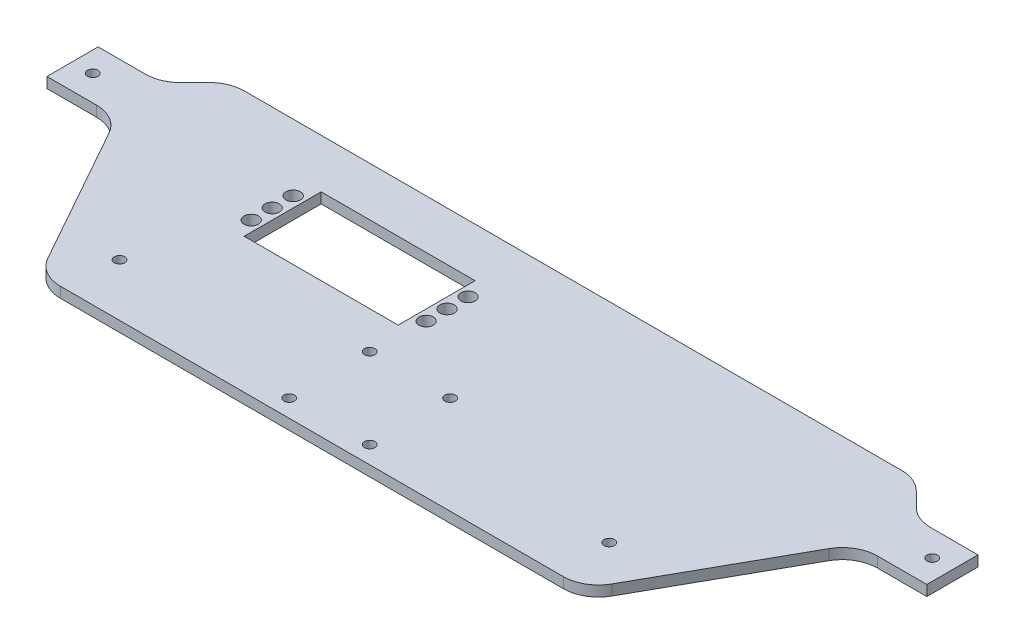
SolidWorks part; units mm, degrees
ref_plane "Alzado" through (0, 0, 0) normal (0, 0, 1) x (1, 0, 0)
ref_plane "Planta" through (0, 0, 0) normal (0, 1, 0) x (1, 0, 0)
ref_plane "Vista lateral" through (0, 0, 0) normal (1, 0, 0) x (0, 0, -1)
sketch "Croquis1" plane through (0, 0, 0) normal (0, 1, 0) x (1, 0, 0)
  line L0 (-27.8825, 0) -> (38.5584, 0) construction
  line L1 (-88.1, 42.3182) -> (88.1, 42.3182)
  line L2 (-77.75, -42.3182) -> (77.75, -42.3182)
  line L3 (-88.1, 42.3182) -> (-108.1, 22.3182)
  line L4 (-108.1, 22.3182) -> (-127.75, 22.3182)
  line L5 (0, 0) -> (0, 27.7067) construction
  line L6 (-127.75, 22.3182) -> (-127.75, 7.6818)
  line L7 (-127.75, 7.6818) -> (-105.75, 7.6818)
  line L8 (-105.75, 7.6818) -> (-77.75, -42.3182)
  line L9 (88.1, 42.3182) -> (108.1, 22.3182)
  line L10 (108.1, 22.3182) -> (127.75, 22.3182)
  line L11 (127.75, 22.3182) -> (127.75, 7.6818)
  line L12 (127.75, 7.6818) -> (105.75, 7.6818)
  line L13 (105.75, 7.6818) -> (77.75, -42.3182)
  dimension "D1" = 255.5
  dimension "D2" = 84.6363
  dimension "D3" = 19.65
  dimension "D4" = 22
  dimension "D5" = 22
  dimension "D6" = 50
  dimension "D7" = 50
  dimension "D8" = 50
  dimension "D9" = 20
  dimension "D10" = 20
  dimension "D11" = 19.65
extrude "Saliente-Extruir1" add sketch "Croquis1" along normal blind 3
fillet "Redondeo1" radius 10 8 edges at (88.1, 1.5, -42.3182) (-88.1, 1.5, -42.3182) (-77.75, 1.5, 42.3182) (77.75, 1.5, 42.3182) (108.1, 1.5, -22.3182) (105.75, 1.5, -7.6818) (-105.75, 1.5, -7.6818) (-108.1, 1.5, -22.3182)
sketch "Croquis2" plane through (0, 3, 0) normal (0, 1, 0) x (1, 0, 0)
  line L0 (0, 0) -> (0, -87.7887) construction
  line L1 (-119.9961, 22.3182) -> (-119.9961, 40.4374) construction
  line L2 (-112.2421, 22.3182) -> (-127.75, 22.3182) construction
  line L3 (-127.75, 15) -> (-123.2915, 15) construction
  line L4 (-127.75, 22.3182) -> (-127.75, 7.6818) construction
  line L5 (119.9961, 22.3182) -> (119.9961, 29.1715) construction
  line L6 (127.75, 22.3182) -> (112.2421, 22.3182) construction
  line L7 (115.6048, 15) -> (126.3231, 15) construction
  line L8 (83.9579, 42.3182) -> (-83.9579, 42.3182) construction
  line L9 (-57, 17.3182) -> (-15, 17.3182)
  line L10 (-71.8888, -42.3182) -> (71.8888, -42.3182) construction
  line L11 (-15, 17.3182) -> (-15, -2.6818)
  line L12 (-15, -2.6818) -> (-57, -2.6818)
  line L13 (-57, -2.6818) -> (-57, 17.3182)
  line L14 (-57, 7.3182) -> (-2.6959, 7.3182) construction
  line L15 (-36, 17.3182) -> (-36, 33.9331) construction
  line L16 (-11, 7.3182) -> (-11, 14.1752) construction
  line L17 (-61, 7.3182) -> (-61, 4.4352) construction
  circle A0 centre (70, -27.3182) radius 1.5
  circle A1 centre (-70, -27.3182) radius 1.5
  circle A2 centre (-119.9961, 15) radius 1.5
  circle A3 centre (119.9961, 15) radius 1.5
  circle A6 centre (-11.5, -14.3182) radius 1.5
  circle A7 centre (11.5, -14.3182) radius 1.5
  circle A8 centre (-11.5, -37.3182) radius 1.5
  circle A9 centre (11.5, -37.3182) radius 1.5
  circle A10 centre (-61, 7.3182) radius 2.05
  circle A11 centre (-11, 7.3182) radius 2.05
  circle A12 centre (-61, 13.3182) radius 2.05
  circle A13 centre (-61, 1.3182) radius 2.05
  circle A14 centre (-11, 13.3182) radius 2.05
  circle A15 centre (-11, 1.3182) radius 2.05
  dimension "D1" = 3
  dimension "D2" = 3
  dimension "D10" = 3
  dimension "D11" = 3
  dimension "D17" = 3
  dimension "D18" = 3
  dimension "D19" = 3
  dimension "D20" = 3
  dimension "D25" = 50
  dimension "D27" = 4.1
  dimension "D28" = 4.1
  dimension "D29" = 4.1
  dimension "D30" = 4.1
  dimension "D31" = 4.1
  dimension "D32" = 4.1
  dimension "D9" = 140
  dimension "D12" = 15
  dimension "D13" = 23
  dimension "D14" = 23
  dimension "D15" = 5
  dimension "D16" = 23
  dimension "D21" = 42
  dimension "D22" = 20
  dimension "D23" = 30
  dimension "D24" = 25
  dimension "D26" = 50
  dimension "D33" = 6
  dimension "D34" = 6
  dimension "D35" = 6
  dimension "D36" = 6
extrude "Cortar-Extruir1" cut sketch "Croquis2" against normal through all
sketch "Croquis3" plane through (0, 3, 0) normal (0, 1, 0) x (1, 0, 0)
  line L0 (-123.75, 22.3182) -> (-123.75, 7.6818)
  line L1 (-112.2421, 22.3182) -> (-127.75, 22.3182) construction
  line L2 (-127.75, 7.6818) -> (-111.6112, 7.6818) construction
  line L3 (-123.75, 7.6818) -> (-127.75, 7.6818)
  line L4 (-127.75, 7.6818) -> (-127.75, 22.3182)
  line L5 (-127.75, 22.3182) -> (-123.75, 22.3182)
  line L6 (127.75, 7.6818) -> (127.75, 22.3182)
  line L7 (127.75, 22.3182) -> (123.75, 22.3182)
  line L8 (127.75, 22.3182) -> (112.2421, 22.3182) construction
  line L9 (123.75, 22.3182) -> (123.75, 7.6818)
  line L10 (111.6112, 7.6818) -> (127.75, 7.6818) construction
  line L11 (123.75, 7.6818) -> (127.75, 7.6818)
  dimension "D1" = 4
  dimension "D2" = 4
extrude "Cortar-Extruir2" cut sketch "Croquis3" against normal through all
sketch "Croquis4" plane through (0, 3, 0) normal (0, 1, 0) x (1, 0, 0)
  line L0 (-36, 17.3182) -> (-36, -16.9775) construction
  line L1 (-15, 17.3182) -> (-57, 17.3182) construction
  line L2 (-57, 7.3182) -> (-47.1795, 7.3182) construction
  line L3 (-57, 17.3182) -> (-57, -2.6818) construction
  line L4 (-58, 18.3182) -> (-58, -3.6818)
  line L5 (-58, -3.6818) -> (-14, -3.6818)
  line L6 (-14, -3.6818) -> (-14, 18.3182)
  line L7 (-58, 18.3182) -> (-14, 18.3182)
  line L8 (-15, -2.6818) -> (-15, 17.3182) construction
  line L9 (-57, -2.6818) -> (-15, -2.6818) construction
  dimension "D1" = 1
  dimension "D2" = 1
  dimension "D3" = 1
  dimension "D4" = 1
extrude "Cortar-Extruir3" cut sketch "Croquis4" against normal through all
sketch "Croquis5" plane through (0, 3, 0) normal (0, 1, 0) x (1, 0, 0)
  line L0 (-63.75, 42.3182) -> (-38.75, 32.3182)
  line L1 (83.9579, 42.3182) -> (-83.9579, 42.3182) construction
  line L2 (-38.75, 32.3182) -> (38.75, 32.3182)
  line L3 (38.75, 32.3182) -> (63.75, 42.3182)
  line L4 (63.75, 42.3182) -> (-63.75, 42.3182)
  line L5 (-123.75, 7.6818) -> (-123.75, 22.3182) construction
  line L6 (123.75, 22.3182) -> (123.75, 7.6818) construction
  line L7 (0, 42.3182) -> (0, 71.9714) construction
  dimension "D1" = 60
  dimension "D2" = 60
  dimension "D3" = 10
  dimension "D4" = 25
extrude "Cortar-Extruir4" cut sketch "Croquis5" against normal through all
fillet "Redondeo2" radius 20 4 edges at (63.75, 1.5, -42.3182) (-63.75, 1.5, -42.3182) (-38.75, 1.5, -32.3182) (38.75, 1.5, -32.3182)
sketch "Croquis6" plane through (0, 3, 0) normal (0, 1, 0) x (1, 0, 0)
  line L0 (-34.8984, 32.3182) -> (-98.1, 32.3182)
  line L1 (-91.0289, 39.3892) -> (-105.1711, 25.2471) construction
  line L2 (-98.1, 50.6044) -> (105.4279, 50.6044)
  line L3 (105.4279, 50.6044) -> (105.4279, 32.3182)
  line L4 (105.4279, 32.3182) -> (-34.8984, 32.3182)
  line L5 (-98.1, 50.6044) -> (-98.1, 32.3182)
extrude "Cortar-Extruir5" cut sketch "Croquis6" against normal blind 10
fillet "Redondeo3" radius 10 2 edges at (98.1, 1.5, -32.3182) (-98.1, 1.5, -32.3182)
sketch "Croquis7" plane through (-123.75, 0, 0) normal (-1, 0, 0) x (0, 0, 1)
  line L4 (-7.6818, 3) -> (-22.3182, 3)
  line L5 (-22.3182, 3) -> (-22.3182, 0)
  line L6 (-22.3182, 0) -> (-7.6818, 0)
  line L7 (-7.6818, 0) -> (-7.6818, 3)
  line L8 (-7.6818, 3) -> (-22.3182, 3)
  line L9 (-22.3182, 3) -> (-22.3182, 0)
  line L10 (-22.3182, 0) -> (-7.6818, 0)
  line L11 (-7.6818, 0) -> (-7.6818, 3)
  dimension "D1" = 0
extrude "Saliente-Extruir2" add sketch "Croquis7" along normal blind 2
sketch "Croquis8" plane through (123.75, 0, 0) normal (1, 0, 0) x (0, 0, -1)
  line L4 (22.3182, 3) -> (7.6818, 3)
  line L5 (7.6818, 3) -> (7.6818, 0)
  line L6 (7.6818, 0) -> (22.3182, 0)
  line L7 (22.3182, 0) -> (22.3182, 3)
  line L8 (22.3182, 3) -> (7.6818, 3)
  line L9 (7.6818, 3) -> (7.6818, 0)
  line L10 (7.6818, 0) -> (22.3182, 0)
  line L11 (22.3182, 0) -> (22.3182, 3)
  dimension "D1" = 0
extrude "Saliente-Extruir3" add sketch "Croquis8" along normal blind 2
